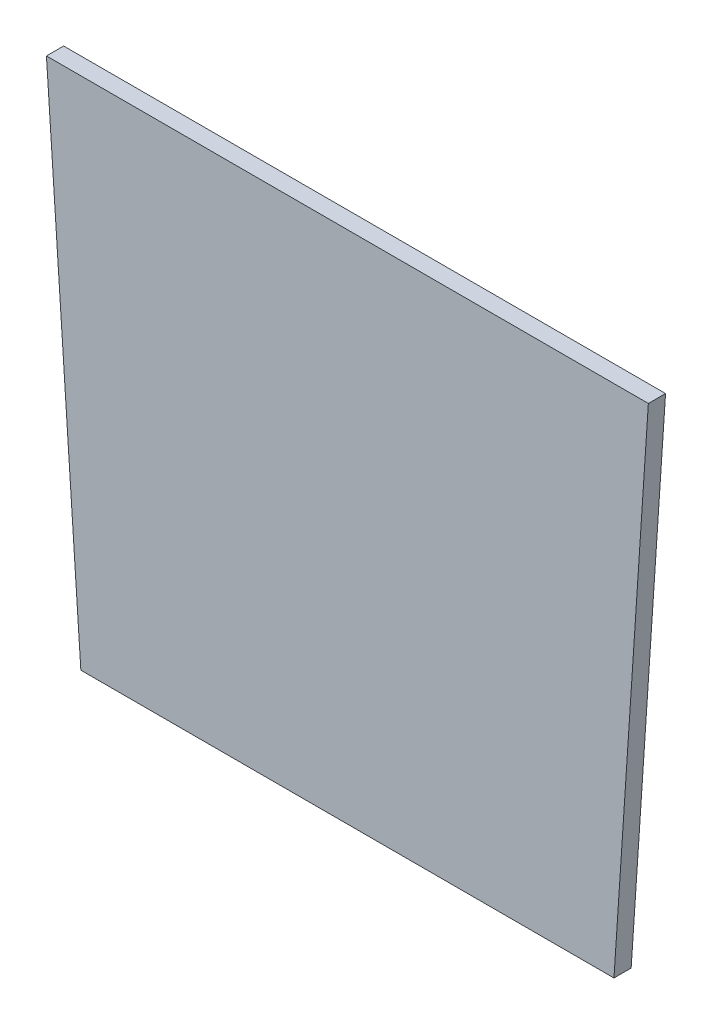
SolidWorks part; units mm, degrees
ref_plane "Płaszczyzna przednia" through (0, 0, 0) normal (0, 0, 1) x (1, 0, 0)
ref_plane "Płaszczyzna górna" through (0, 0, 0) normal (0, 1, 0) x (1, 0, 0)
ref_plane "Płaszczyzna prawa" through (0, 0, 0) normal (1, 0, 0) x (0, 0, -1)
sketch "Szkic1" plane through (0, 0, 0) normal (0, 0, 1) x (1, 0, 0)
  line L0 (-175, 149.6663) -> (175, 149.6663)
  line L1 (175, 149.6663) -> (155, -149.6663)
  line L2 (155, -149.6663) -> (-155, -149.6663)
  line L3 (-155, -149.6663) -> (-175, 149.6663)
  point P2 (0, 149.6663)
  point P5 (0, -149.6663)
  point P7 (-165, 0)
  dimension "D1" = 350
  dimension "D2" = 310
  dimension "D3" = 300
extrude "Dodanie-wyciągnięcie1" add sketch "Szkic1" along normal blind 10
